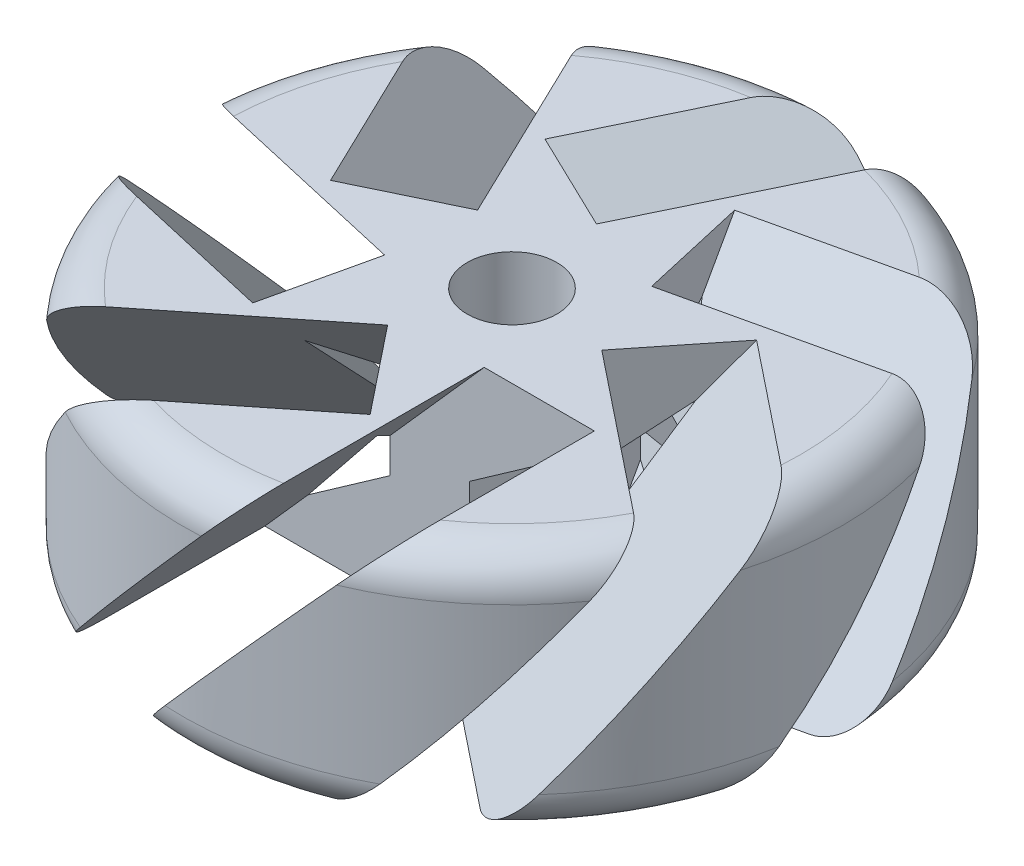
SolidWorks part; units mm, degrees
ref_plane "Front Plane" through (0, 0, 0) normal (0, 0, 1) x (1, 0, 0)
ref_plane "Top Plane" through (0, 0, 0) normal (0, 1, 0) x (1, 0, 0)
ref_plane "Right Plane" through (0, 0, 0) normal (1, 0, 0) x (0, 0, -1)
sketch "Sketch1" plane through (0, 0, 0) normal (0, 1, 0) x (1, 0, 0)
  circle A0 centre (0, 0) radius 25.4
  dimension "D1" = 50.8
extrude "Boss-Extrude1" add sketch "Sketch1" along normal blind 19.05
hole_wizard "5/16-24 Tapped Hole1" positions "Sketch3" profile "Sketch2" tap size "5/16-24" standard "ANSI Inch" end condition up to next
sketch "Sketch3" plane through (0, 19.05, 0) normal (0, 1, 0) x (1, 0, 0)
  point P0 (0, 0)
sketch "Sketch2" plane through (0, 19.05, 0) normal (1, 0, 0) x (0, 0, 1)
  line L0 (0, 0) -> (0, 19.05)
  line L1 (0, 19.05) -> (3.4544, 19.05)
  line L2 (3.4544, 19.05) -> (3.4544, 0)
  line L5 (3.4544, 0) -> (0, 0)
  line L11 (0, -6.35) -> (0, 107.95) construction
  dimension "Thru Tap Drill Dia." = 6.9088
  dimension "Thru Tap Drill Depth" = 19.05
cosmetic thread "Hole Thread1" parameters "D2"=7.9375
sketch "Sketch4" plane through (0, 0, 0) normal (0, 0, 1) x (1, 0, 0)
  line L0 (7.951, 23.2654) -> (-12.7, 0)
  line L1 (7.951, 23.2654) -> (12.7, 19.05)
  line L2 (-12.7, 0) -> (-7.951, -4.2154)
  line L3 (12.7, 19.05) -> (-7.951, -4.2154)
  line L4 (25.4, 0) -> (25.4, 19.05) construction
  line L5 (-25.4, 19.05) -> (-25.4, 0) construction
  line L6 (-25.4, 0) -> (25.4, 0) construction
  line L7 (25.4, 19.05) -> (-25.4, 19.05) construction
  dimension "D1" = 6.35
  dimension "D2" = 12.7
  dimension "D3" = 12.7
fillet "Fillet1" radius 3.175 2 edges at (0, 19.05, 25.4) (0, 0, 25.4)
ref_plane "Plane1" through (0, 0, 28.575) normal (0, 0, 1) x (1, 0, 0)
sketch "Sketch5" plane through (0, 0, 28.575) normal (0, 0, 1) x (1, 0, 0)
  line L4 (7.951, 23.2654) -> (-12.7, 0)
  line L5 (-12.7, 0) -> (-7.951, -4.2154)
  line L6 (-7.951, -4.2154) -> (12.7, 19.05)
  line L7 (12.7, 19.05) -> (7.951, 23.2654)
  line L8 (7.951, 23.2654) -> (-12.7, 0)
  line L9 (-12.7, 0) -> (-7.951, -4.2154)
  line L10 (-7.951, -4.2154) -> (12.7, 19.05)
  line L11 (12.7, 19.05) -> (7.951, 23.2654)
  dimension "D1" = 0
extrude "Cut-Extrude1" cut sketch "Sketch5" against normal blind 22.225 contours L10 L11 L8 L9
pattern_circular "CirPattern1" count 7 over 360 about axis through (0, 0, 0) along (0, 1, 0) of "Cut-Extrude1"
